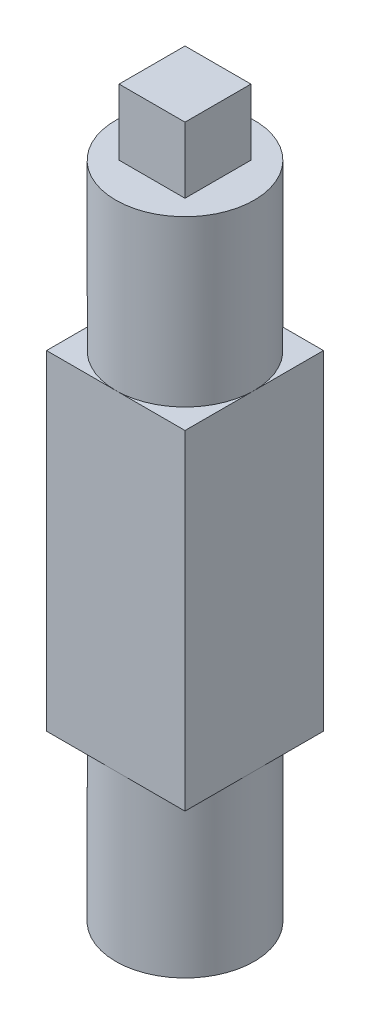
SolidWorks part; units mm, degrees
ref_plane "Front Plane" through (0, 0, 0) normal (0, 0, 1) x (1, 0, 0)
ref_plane "Top Plane" through (0, 0, 0) normal (0, 1, 0) x (1, 0, 0)
ref_plane "Right Plane" through (0, 0, 0) normal (1, 0, 0) x (0, 0, -1)
sketch "Sketch2" plane through (0, 0, 0) normal (0, 1, 0) x (1, 0, 0)
  circle A0 centre (0, 0) radius 10.5
  dimension "D1" = 21
extrude "Boss-Extrude1" add sketch "Sketch2" along normal blind 25
sketch "Sketch3" plane through (0, 25, 0) normal (0, 1, 0) x (1, 0, 0)
  line L1 (10.5, -10.5) -> (-10.5, -10.5)
  line L2 (10.5, -10.5) -> (10.5, 10.5)
  line L3 (10.5, 10.5) -> (-10.5, 10.5)
  line L4 (-10.5, -10.5) -> (-10.5, 10.5)
  line L5 (10.5, -10.5) -> (-10.5, 10.5) construction
  line L6 (10.5, 10.5) -> (-10.5, -10.5) construction
  point P0 (0, 0)
  dimension "D1" = 21
  dimension "D2" = 21
extrude "Boss-Extrude2" add sketch "Sketch3" along normal blind 50
sketch "Sketch4" plane through (0, 75, 0) normal (0, 1, 0) x (1, 0, 0)
  circle A0 centre (0, 0) radius 10.5 construction
  circle A1 centre (0, 0) radius 10.5
extrude "Boss-Extrude3" add sketch "Sketch4" along normal blind 25
sketch "Sketch5" plane through (0, 100, 0) normal (0, 1, 0) x (1, 0, 0)
  line L1 (-5, 5) -> (5, 5)
  line L2 (-5, 5) -> (-5, -5)
  line L3 (-5, -5) -> (5, -5)
  line L4 (5, 5) -> (5, -5)
  line L5 (-5, 5) -> (5, -5) construction
  line L6 (-5, -5) -> (5, 5) construction
  point P0 (0, 0)
  dimension "D1" = 10
  dimension "D2" = 10
extrude "Boss-Extrude4" add sketch "Sketch5" along normal blind 10
sketch "Sketch6" plane through (-10.5, 0, 0) normal (-1, 0, 0) x (0, 0, 1)
  circle A0 centre (0, 56.2031) radius 4
  dimension "D1" = 8
extrude "Cut-Extrude1" cut sketch "Sketch6" against normal blind 18
sketch "Sketch7" plane through (0, 0, 0) normal (0, -1, 0) x (1, 0, 0)
  circle A0 centre (0, 0) radius 6.5
  arc A1 (0, 10.5) -> (-10.5, 0) centre (0, 0) ccw construction
  dimension "D1" = 4
extrude "Cut-Extrude2" cut sketch "Sketch7" against normal blind 65
